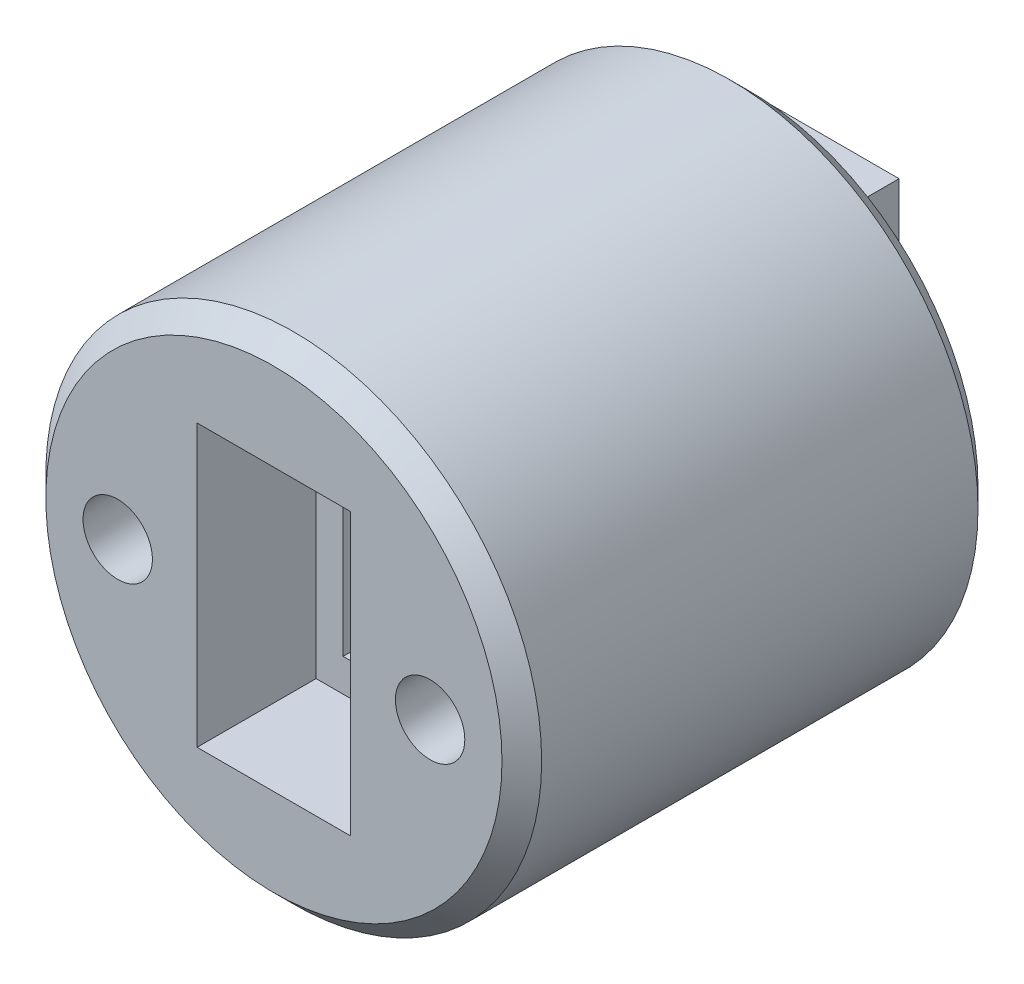
SolidWorks part; units mm, degrees
material "ABS"
ref_plane "Alzado" through (0, 0, 0) normal (0, 0, 1) x (1, 0, 0)
ref_plane "Planta" through (0, 0, 0) normal (0, 1, 0) x (1, 0, 0)
ref_plane "Vista lateral" through (0, 0, 0) normal (1, 0, 0) x (0, 0, -1)
sketch "Croquis1" plane through (0, 0, 0) normal (0, 0, 1) x (1, 0, 0)
  circle A0 centre (0, 0) radius 12.5
  dimension "D1" = 25
extrude "Saliente-Extruir1" add sketch "Croquis1" along normal blind 24
sketch "Croquis2" plane through (0, 0, 24) normal (0, 0, 1) x (1, 0, 0)
  line L1 (-3.873, 7.0812) -> (3.873, 7.0812)
  line L2 (-3.873, 7.0812) -> (-3.873, -7.0812)
  line L3 (-3.873, -7.0812) -> (3.873, -7.0812)
  line L4 (3.873, 7.0812) -> (3.873, -7.0812)
  line L5 (-3.873, 7.0812) -> (3.873, -7.0812) construction
  line L6 (-3.873, -7.0812) -> (3.873, 7.0812) construction
  point P0 (0, 0)
extrude "Cortar-Extruir1" cut sketch "Croquis2" against normal blind 6
sketch "Croquis3" plane through (0, 0, 0) normal (0, 0, -1) x (-1, 0, 0)
  line L1 (-3.5208, 7.4439) -> (3.5208, 7.4439)
  line L2 (-3.5208, 7.4439) -> (-3.5208, -7.4439)
  line L3 (-3.5208, -7.4439) -> (3.5208, -7.4439)
  line L4 (3.5208, 7.4439) -> (3.5208, -7.4439)
  line L5 (-3.5208, 7.4439) -> (3.5208, -7.4439) construction
  line L6 (-3.5208, -7.4439) -> (3.5208, 7.4439) construction
  point P0 (0, 0)
extrude "Saliente-Extruir2" add sketch "Croquis3" along normal blind 5
chamfer "Chaflán1" distance 1 angle 45 4 edges at (-3.5208, 0, -5) (0, -7.4439, -5) (0, 7.4439, -5) (3.5208, 0, -5)
chamfer "Chaflán2" distance 1 angle 45 1 edges at (12.5, 0, 0)
sketch "Croquis4" plane through (0, 0, 24) normal (0, 0, 1) x (1, 0, 0)
  line L0 (0, 17.1892) -> (0, -16.9535) construction
  circle A0 centre (-7.875, 0) radius 1.75
  circle A1 centre (7.875, 0) radius 1.75
  point P7 (0, 0)
  dimension "D2" = 3.5
  dimension "D1" = 15.75
extrude "Cortar-Extruir2" cut sketch "Croquis4" against normal through all
chamfer "Chaflán3" distance 1 angle 45 1 edges at (12.5, 0, 24)
sketch "Croquis5" plane through (0, 0, 18) normal (0, 0, 1) x (1, 0, 0)
  line L1 (-2.5148, 5.4321) -> (2.5148, 5.4321)
  line L2 (-2.5148, 5.4321) -> (-2.5148, -5.4321)
  line L3 (-2.5148, -5.4321) -> (2.5148, -5.4321)
  line L4 (2.5148, 5.4321) -> (2.5148, -5.4321)
  line L5 (-2.5148, 5.4321) -> (2.5148, -5.4321) construction
  line L6 (-2.5148, -5.4321) -> (2.5148, 5.4321) construction
  point P0 (0, 0)
extrude "Cortar-Extruir3" cut sketch "Croquis5" against normal through all
